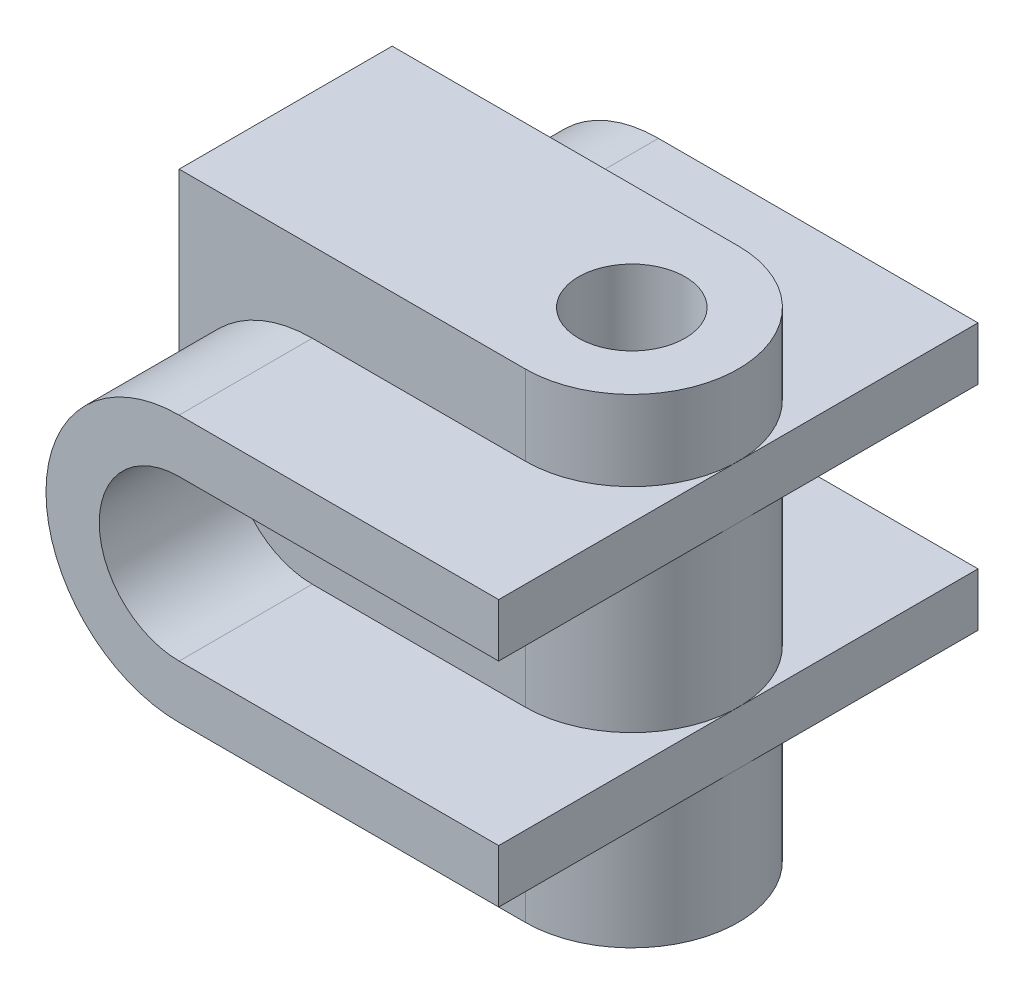
SolidWorks part; units mm, degrees
ref_plane "Front" through (0, 0, 0) normal (0, 0, 1) x (1, 0, 0)
ref_plane "Top" through (0, 0, 0) normal (0, 1, 0) x (1, 0, 0)
ref_plane "Right" through (0, 0, 0) normal (1, 0, 0) x (0, 0, -1)
other "Configuration Table"
sketch "Sketch1" plane through (0, 0, 0) normal (0, 0, 1) x (1, 0, 0)
  line L0 (0, -15) -> (-60, -15)
  line L1 (-60, -65) -> (0, -65)
  arc A0 (-60, -15) -> (-60, -65) centre (-60, -40) ccw
  dimension "D3" = 25
  dimension "D1" = 15
  dimension "D2" = 60
extrude "Extrude-Thin1" add sketch "Sketch1" along normal blind 90 thin thin type one direction reverse wall 10
sketch "Sketch2" plane through (0, 0, 0) normal (0, 1, 0) x (1, 0, 0)
  line L0 (-85, -25) -> (-85, -65)
  line L1 (-85, 0) -> (-85, -90) construction
  line L2 (-85, -65) -> (-20, -65)
  line L3 (-20, -25) -> (-85, -25)
  line L4 (0, -90) -> (0, 0) construction
  arc A0 (-20, -65) -> (-20, -25) centre (-20, -45) ccw
  circle A1 centre (-20, -45) radius 10
  dimension "D2" = 25
  dimension "D3" = 20
  dimension "D1" = 40
extrude "Boss-Extrude1" add sketch "Sketch2" against normal blind 90 separate body
